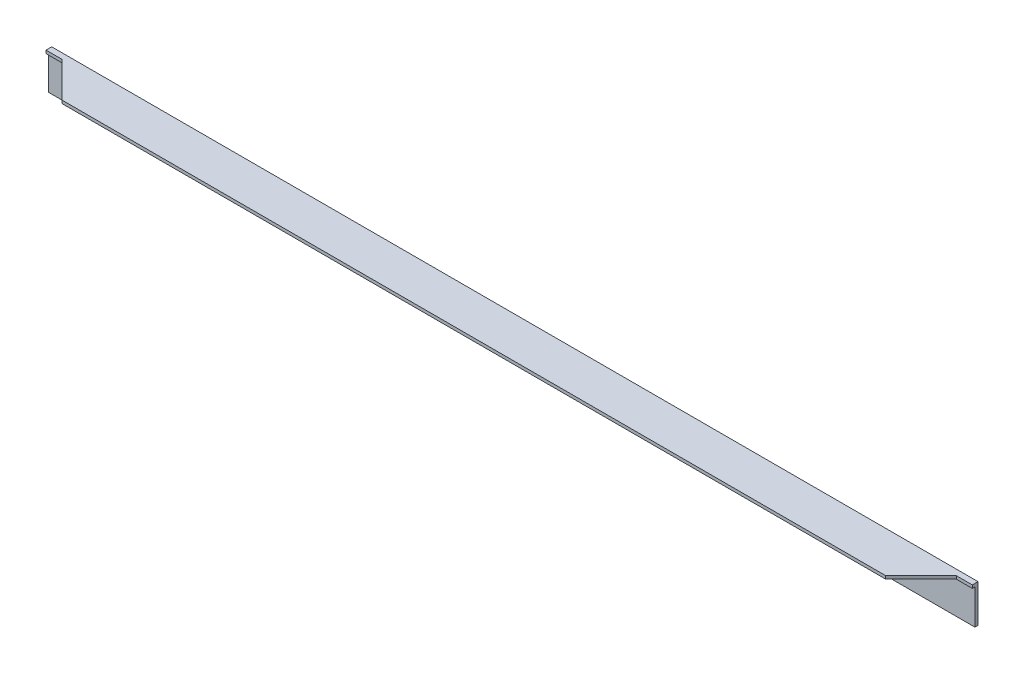
SolidWorks part; units mm, degrees
ref_plane "前视" through (0, 0, 0) normal (0, 0, 1) x (1, 0, 0)
ref_plane "上视" through (0, 0, 0) normal (0, 1, 0) x (1, 0, 0)
ref_plane "右视" through (0, 0, 0) normal (1, 0, 0) x (0, 0, -1)
sketch "草图1" plane through (0, 0, 0) normal (0, 0, 1) x (1, 0, 0)
  line L0 (0, 0) -> (0, 1201.1794) construction
  line L1 (-1220, 0) -> (1220, 0)
  line L2 (-1220, 0) -> (-1220, 100)
  line L3 (-1220, 100) -> (1220, 100)
  line L4 (1220, 0) -> (1220, 100)
  line L5 (1238.3745, 40) -> (698.9756, 40) construction
  line L6 (692.2249, 40) -> (138.717, 40) construction
  line L7 (0, 0) -> (804.1445, 0) construction
  line L8 (1170, -74.0451) -> (1170, 582.7434) construction
  line L10 (1090, -107.6037) -> (1090, 582.7434) construction
  line L11 (1414, 542.8394) -> (1414, -805.3158) construction
  line L12 (138.717, 40) -> (-430.5746, 40) construction
  line L13 (-1414, 582.7434) -> (-1414, -1649.9569) construction
  dimension "D4" = 50
  dimension "D5" = 80
  dimension "D1" = 2440
  dimension "D2" = 100
  dimension "D3" = 40
extrude "基体-拉伸" add sketch "草图1" along normal blind 8
sketch "草图2" plane through (0, 0, 8) normal (0, 0, 1) x (1, 0, 0)
  line L0 (1220, 0) -> (1220, 100) construction
  line L1 (-1220, 100) -> (1220, 100)
  line L2 (-1220, 100) -> (-1220, 92)
  line L3 (-1220, 92) -> (1220, 92)
  line L4 (1220, 100) -> (1220, 92)
  dimension "D1" = 8
extrude "凸台-拉伸1" add sketch "草图2" along normal blind 100
sketch "草图3" plane through (0, 100, 0) normal (0, 1, 0) x (-1, 0, 0)
  line L2 (-1220, 108) -> (-1220, 0) construction
  line L3 (-1220, 0) -> (1220, 0) construction
  line L4 (-1220, 108) -> (1220, 108) construction
  line L5 (-1085, 108) -> (-1178, 15)
  line L6 (-1085, 108) -> (-1220, 108)
  line L7 (-1220, 108) -> (-1220, 15)
  line L8 (-1220, 15) -> (-1178, 15)
  line L9 (0, 868.9044) -> (0, -812.8803) construction
  line L10 (1220, 108) -> (1220, 0) construction
  line L11 (1220, 15) -> (1178, 15)
  line L12 (1220, 108) -> (1220, 15)
  line L13 (1085, 108) -> (1220, 108)
  line L14 (1085, 108) -> (1178, 15)
  point P0 (-1220, 15)
  point P5 (-1085, 108)
  dimension "D1" = 15
  dimension "D2" = 135
  dimension "D3" = 45
extrude "切除-拉伸1" cut sketch "草图3" against normal through all
